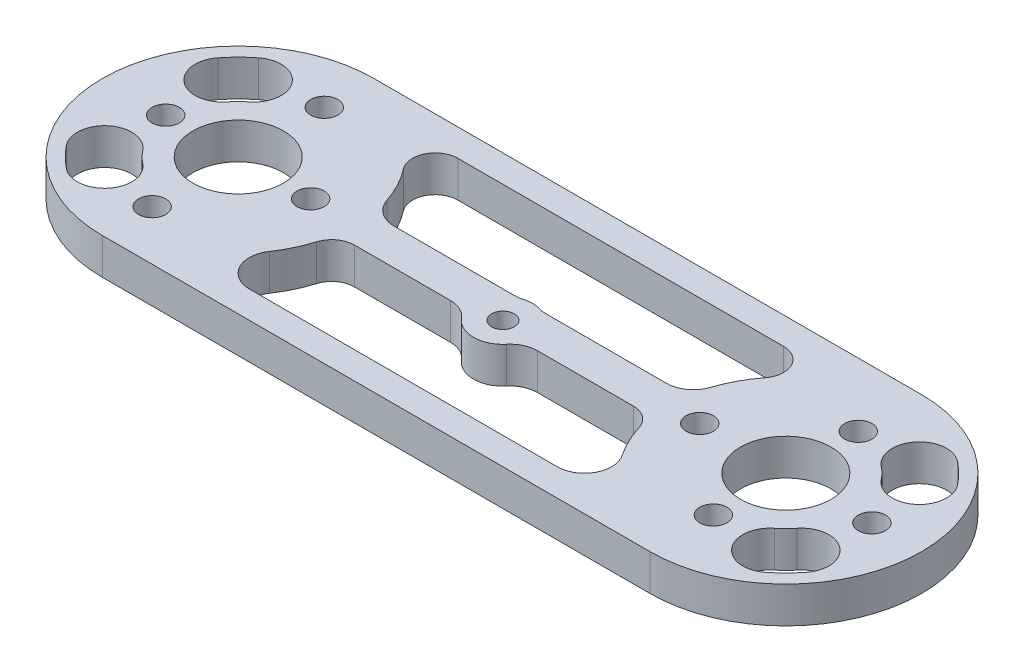
SolidWorks part; units mm, degrees
material "碳板"
ref_plane "前视基准面" through (0, 0, 0) normal (0, 0, 1) x (1, 0, 0)
ref_plane "上视基准面" through (0, 0, 0) normal (0, 1, 0) x (1, 0, 0)
ref_plane "右视基准面" through (0, 0, 0) normal (1, 0, 0) x (0, 0, -1)
sketch "草图1" plane through (0, 0, 0) normal (0, 1, 0) x (1, 0, 0)
  line L0 (0, 14.5411) -> (0, -16.0863) construction
  line L1 (-30.225, 0) -> (30.225, 0) construction
  line L2 (-30.225, 15) -> (30.225, 15)
  line L3 (-30.225, -15) -> (30.225, -15)
  line L4 (-78.0617, 0) -> (54.2175, 0) construction
  line L5 (-30.225, 15) -> (-30.225, -15) construction
  line L6 (30.225, 15) -> (30.225, -15) construction
  circle A0 centre (-30.225, 0) radius 5
  circle A1 centre (30.225, 0) radius 5
  arc A2 (-30.225, 15) -> (-30.225, -15) centre (-30.225, 0) ccw
  arc A3 (30.225, -15) -> (30.225, 15) centre (30.225, 0) ccw
  circle A4 centre (-30.225, 9.5) radius 1.5
  circle A5 centre (-30.225, -9.5) radius 1.5
  circle A6 centre (-38.225, 0) radius 1.5
  circle A7 centre (-22.225, 0) radius 1.5
  circle A9 centre (30.225, 8) radius 1.5
  circle A11 centre (20.725, 0) radius 1.5
  circle A12 centre (39.725, 0) radius 1.5
  circle A13 centre (30.225, -8) radius 1.5
  circle A16 centre (0, -1) radius 1.25
  point P7 (0, 0)
  dimension "D1" = 10
  dimension "D2" = 60.45
  dimension "D3" = 15
  dimension "D4" = 19
  dimension "D5" = 3
  dimension "D6" = 16
  dimension "D7" = 16
  dimension "D8" = 3
  dimension "D10" = 1
  dimension "D12" = 2.5
  dimension "D9" = 19
extrude "凸台-拉伸1" add sketch "草图1" along normal blind 4
sketch "草图2" plane through (0, 4, 0) normal (0, 1, 0) x (1, 0, 0)
  line L0 (-30.225, 0) -> (30.225, 0) construction
  line L1 (-17.3798, -2) -> (17.3798, -2)
  line L2 (-25.225, -12) -> (25.225, -12)
  line L3 (-30.225, -15) -> (30.225, -15) construction
  line L4 (-25.225, 12) -> (25.225, 12)
  line L5 (-17.3798, 2) -> (17.3798, 2)
  circle A0 centre (-30.225, 0) radius 5 construction
  circle A1 centre (-30.225, 0) radius 5 construction
  circle A2 centre (30.225, 0) radius 5 construction
  circle A3 centre (30.225, 0) radius 5 construction
  circle A4 centre (-30.225, 0) radius 13
  circle A5 centre (30.225, 0) radius 13
  circle A8 centre (0, -1) radius 3.25
  circle A9 centre (0, -1) radius 3.25
  dimension "D1" = 8
  dimension "D2" = 4
  dimension "D3" = 3
  dimension "D4" = 2
extrude "切除-拉伸1" cut sketch "草图2" against normal blind 10 contours A5 L4 A4 L5 | A5 L1 A4 L2
fillet "圆角1" radius 2.5 4 edges at (-25.225, 2, -12) (25.225, 2, -12) (-17.3798, 2, 2) (17.3798, 2, 2)
fillet "圆角2" radius 3 8 edges at (17.3798, 2, -2) (-17.3798, 2, -2) (-1.25, 2, -2) (1.25, 2, -2) (3.0923, 2, 2) (-3.0923, 2, 2) (25.225, 2, 12) (-25.225, 2, 12)
sketch "草图3" plane through (0, 4, 0) normal (0, 1, 0) x (1, 0, 0)
  line L0 (-30.225, 0) -> (30.225, 0) construction
  line L1 (0, 24.0435) -> (0, -23.9999) construction
  circle A0 centre (-30.225, 0) radius 13.5
  circle A1 centre (-30.225, 0) radius 7.5
  arc A2 (-30.225, 15) -> (-30.225, -15) centre (-30.225, 0) ccw construction
  circle A3 centre (-30.225, 0) radius 5 construction
  arc A4 (-40.8273, 8.3571) -> (-36.1152, 4.6429) centre (-38.4712, 6.5) ccw
  arc A5 (-38.5821, 10.6023) -> (-34.8679, 5.8902) centre (-36.725, 8.2462) cw
  circle A6 centre (-38.225, 0) radius 1.5 construction
  circle A7 centre (-30.225, 9.5) radius 1.5 construction
  arc A8 (-38.5821, -10.6023) -> (-34.8679, -5.8902) centre (-36.725, -8.2462) ccw
  arc A9 (-40.8273, -8.3571) -> (-36.1152, -4.6429) centre (-38.4712, -6.5) cw
  arc A10 (40.8273, -8.3571) -> (36.1152, -4.6429) centre (38.4712, -6.5) ccw
  arc A11 (38.5821, -10.6023) -> (34.8679, -5.8902) centre (36.725, -8.2462) cw
  arc A12 (38.5821, 10.6023) -> (34.8679, 5.8902) centre (36.725, 8.2462) ccw
  arc A13 (40.8273, 8.3571) -> (36.1152, 4.6429) centre (38.4712, 6.5) cw
  circle A14 centre (30.225, 0) radius 7.5
  circle A15 centre (30.225, 0) radius 13.5
  dimension "D1" = 1.5
  dimension "D2" = 2.5
  dimension "D3" = 6.5
  dimension "D4" = 6.5
extrude "切除-拉伸2" cut sketch "草图3" against normal blind 10 contours A5 A0 A4 A1 | A9 A0 A8 A1 | A15 A10 A14 A11 | A15 A12 A14 A13
chamfer "倒角1" distance 1.5 angle 45 1 edges at (0, 0, 2.25)
